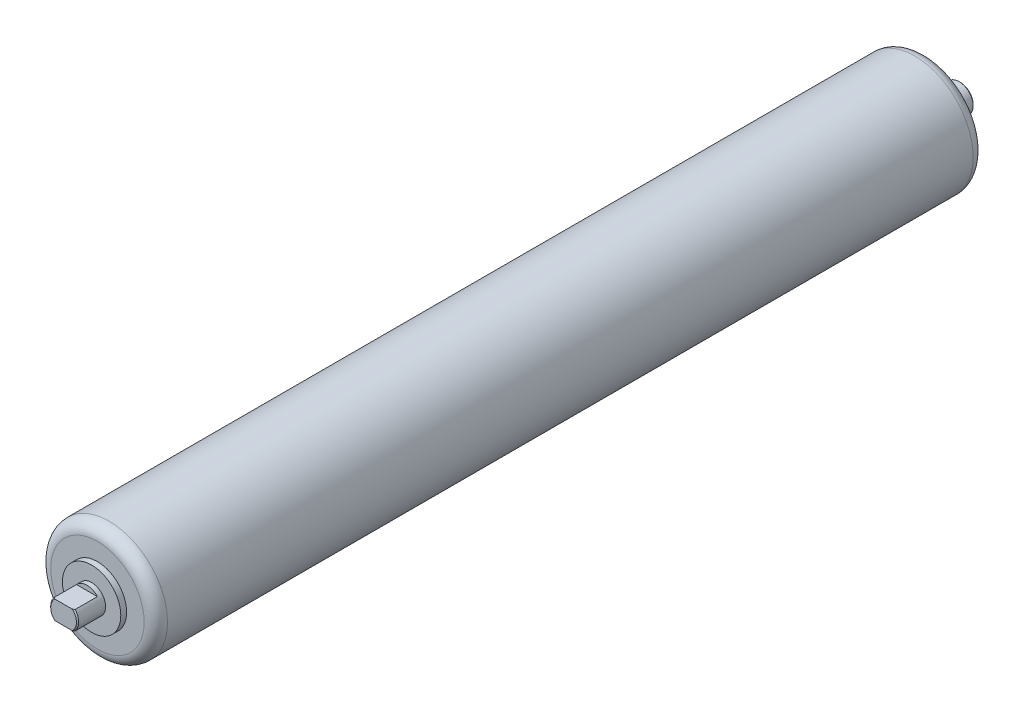
SolidWorks part; units mm, degrees
ref_plane "Front Plane" through (0, 0, 0) normal (0, 0, 1) x (1, 0, 0)
ref_plane "Top Plane" through (0, 0, 0) normal (0, 1, 0) x (1, 0, 0)
ref_plane "Right Plane" through (0, 0, 0) normal (1, 0, 0) x (0, 0, -1)
sketch "Sketch1" plane through (0, 0, 0) normal (0, 1, 0) x (1, 0, 0)
  line L0 (5.5, 14.5) -> (0, 14.5)
  line L1 (0, 14.5) -> (0, -369.5)
  line L2 (0, -369.5) -> (5.5, -369.5)
  line L3 (5.5, -369.5) -> (6, -369)
  line L4 (6, -369) -> (6, -357.5)
  line L5 (6, -357.5) -> (12.5, -357.5)
  line L6 (12.5, -357.5) -> (12.5, -355)
  line L7 (12.5, -355) -> (25, -355)
  line L8 (25, -355) -> (25, 0)
  line L9 (25, 0) -> (12.5, 0)
  line L10 (12.5, 0) -> (12.5, 2.5)
  line L11 (12.5, 2.5) -> (6, 2.5)
  line L12 (6, 2.5) -> (6, 14)
  line L13 (6, 14) -> (5.5, 14.5)
  line L14 (0, 14.5) -> (0, -369.5) construction
revolve "Revolve1" add sketch "Sketch1" angle 360 about L14
fillet "Fillet1" radius 5 2 edges at (25, 0, 355) (25, 0, 0)
sketch "Sketch2" plane through (0, 0, 369.5) normal (0, 0, 1) x (1, 0, 0)
  line L0 (-4.4721, 4) -> (5.9555, 4)
  line L1 (-4.4721, -4) -> (4.4721, -4)
  circle A0 centre (0, 0) radius 6 construction
  arc A1 (4.4721, 4) -> (-4.4721, 4) centre (0, 0) ccw
  arc A2 (-4.4721, -4) -> (4.4721, -4) centre (0, 0) ccw
  circle M3 centre (0, 0) radius 5.5
  dimension "D1" = 8
  dimension "D2" = 4
extrude "Cut-Extrude1" cut sketch "Sketch2" against normal blind 10 contours L0 A1 M3 | L0 M3 | L1 M3 | L1 A2 M3
